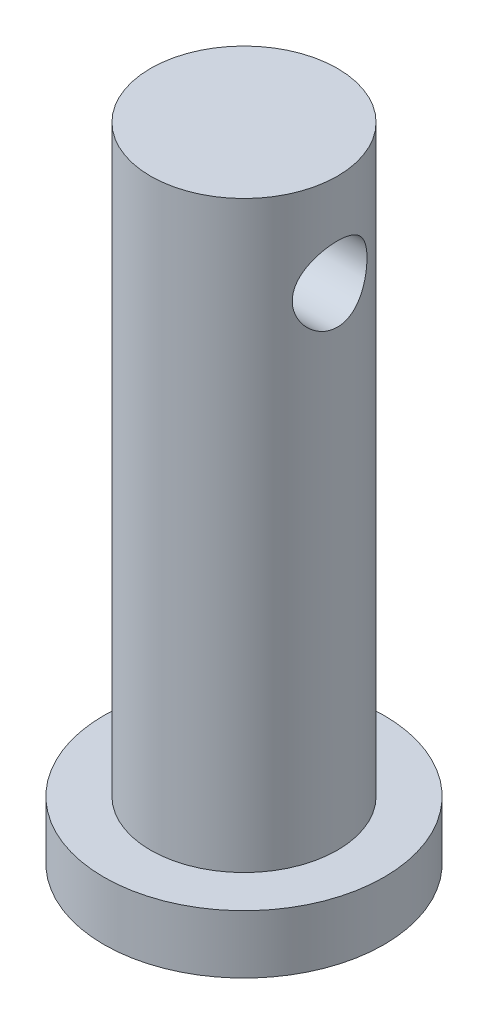
SolidWorks part; units mm, degrees
ref_plane "前视基准面" through (0, 0, 0) normal (0, 0, 1) x (1, 0, 0)
ref_plane "上视基准面" through (0, 0, 0) normal (0, 1, 0) x (1, 0, 0)
ref_plane "右视基准面" through (0, 0, 0) normal (1, 0, 0) x (0, 0, -1)
sketch "草图1" plane through (0, 0, 0) normal (0, 1, 0) x (1, 0, 0)
  circle A0 centre (0, 0) radius 6
  dimension "D1" = 12
extrude "凸台-拉伸1" add sketch "草图1" along normal blind 2.5
sketch "草图2" plane through (0, 2.5, 0) normal (0, 1, 0) x (1, 0, 0)
  circle A0 centre (0, 0) radius 4
  dimension "D1" = 8
extrude "凸台-拉伸2" add sketch "草图2" along normal blind 25
sketch "草图3" plane through (0, 0, 0) normal (1, 0, 0) x (0, 0, -1)
  line L0 (4, 27.5) -> (-4, 27.5) construction
  circle A0 centre (0, 23.5) radius 1.6
  dimension "D1" = 3.2
  dimension "D2" = 4
extrude "切除-拉伸1" cut sketch "草图3" against normal through all both and the other way through all
